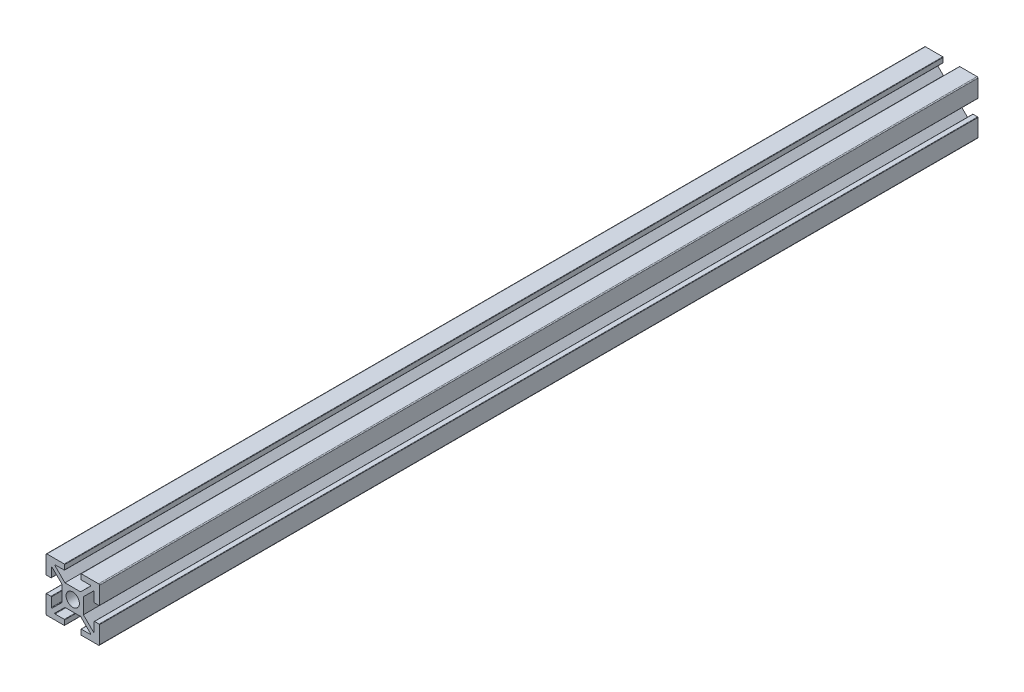
SolidWorks part; units mm, degrees
ref_plane "Front Plane" through (0, 0, 0) normal (0, 0, 1) x (1, 0, 0)
ref_plane "Top Plane" through (0, 0, 0) normal (0, 1, 0) x (1, 0, 0)
ref_plane "Right Plane" through (0, 0, 0) normal (1, 0, 0) x (0, 0, -1)
sketch "Sketch1" plane through (0, 0, 0) normal (0, 0, 1) x (1, 0, 0)
  line L0 (-7.4274, 2.1557) -> (-5.7274, 2.1557)
  line L1 (-0.7274, 9.1557) -> (-7.2274, 9.1557)
  line L2 (-7.5774, 2.3057) -> (-7.5774, 8.8057)
  line L3 (5.4021, 3.1557) -> (-0.4643, 3.1557)
  line L4 (-1.5311, -3.7897) -> (-1.5311, 2.1011)
  line L5 (-5.5774, 2.3057) -> (-5.5774, 5.7419)
  line L6 (-4.1455, 7.1557) -> (-0.7274, 7.1557)
  line L7 (-0.5774, 7.3057) -> (-0.5774, 9.0057)
  line L8 (-5.5774, 7.1557) -> (-1.5311, 3.1557) construction
  line L9 (-5.3219, 5.8486) -> (-1.5311, 2.1011)
  line L10 (-4.2509, 6.899) -> (-0.4643, 3.1557)
  line L11 (10.5152, 7.1557) -> (6.4689, 3.1557) construction
  line L12 (2.4689, -0.8443) -> (2.4689, 10.8443) construction
  line L13 (2.4689, -0.8443) -> (-12.5152, -0.8443) construction
  line L14 (9.1887, 6.899) -> (5.4021, 3.1557)
  line L15 (10.2598, 5.8486) -> (6.4689, 2.1011)
  line L16 (5.5152, 7.3057) -> (5.5152, 9.0057)
  line L17 (9.0833, 7.1557) -> (5.6652, 7.1557)
  line L18 (10.5152, 2.3057) -> (10.5152, 5.7419)
  line L19 (6.4689, -3.7897) -> (6.4689, 2.1011)
  line L20 (12.5152, 2.3057) -> (12.5152, 8.8057)
  line L21 (5.6652, 9.1557) -> (12.1652, 9.1557)
  line L22 (12.3652, 2.1557) -> (10.6652, 2.1557)
  line L23 (10.5152, -8.8443) -> (6.4689, -4.8443) construction
  line L24 (-5.5774, -8.8443) -> (-1.5311, -4.8443) construction
  line L25 (12.3652, -3.8443) -> (10.6652, -3.8443)
  line L26 (5.6652, -10.8443) -> (12.1652, -10.8443)
  line L27 (12.5152, -3.9943) -> (12.5152, -10.4943)
  line L28 (10.5152, -3.9943) -> (10.5152, -7.4305)
  line L29 (9.0833, -8.8443) -> (5.6652, -8.8443)
  line L30 (5.5152, -8.9943) -> (5.5152, -10.6943)
  line L31 (10.2598, -7.5372) -> (6.4689, -3.7897)
  line L32 (9.1887, -8.5876) -> (5.4021, -4.8443)
  line L33 (-4.2509, -8.5876) -> (-0.4643, -4.8443)
  line L34 (-5.3219, -7.5372) -> (-1.5311, -3.7897)
  line L35 (-0.5774, -8.9943) -> (-0.5774, -10.6943)
  line L36 (-4.1455, -8.8443) -> (-0.7274, -8.8443)
  line L37 (-5.5774, -3.9943) -> (-5.5774, -7.4305)
  line L38 (5.4021, -4.8443) -> (-0.4643, -4.8443)
  line L39 (-7.5774, -3.9943) -> (-7.5774, -10.4943)
  line L40 (-0.7274, -10.8443) -> (-7.2274, -10.8443)
  line L41 (-7.4274, -3.8443) -> (-5.7274, -3.8443)
  circle A0 centre (2.4689, -0.8443) radius 2.5
  arc A1 (-7.5774, 8.8057) -> (-7.2274, 9.1557) centre (-7.2274, 8.8057) cw
  arc A2 (-7.4274, 2.1557) -> (-7.5774, 2.3057) centre (-7.4274, 2.3057) cw
  arc A3 (-5.7274, 2.1557) -> (-5.5774, 2.3057) centre (-5.7274, 2.3057) ccw
  arc A4 (-0.7274, 9.1557) -> (-0.5774, 9.0057) centre (-0.7274, 9.0057) cw
  arc A5 (-0.7274, 7.1557) -> (-0.5774, 7.3057) centre (-0.7274, 7.3057) ccw
  arc A6 (-4.2509, 6.899) -> (-4.1455, 7.1557) centre (-4.1455, 7.0057) cw
  arc A7 (-5.3219, 5.8486) -> (-5.5774, 5.7419) centre (-5.4274, 5.7419) ccw
  arc A8 (10.2598, 5.8486) -> (10.5152, 5.7419) centre (10.3652, 5.7419) cw
  arc A9 (9.1887, 6.899) -> (9.0833, 7.1557) centre (9.0833, 7.0057) ccw
  arc A10 (5.6652, 7.1557) -> (5.5152, 7.3057) centre (5.6652, 7.3057) cw
  arc A11 (5.6652, 9.1557) -> (5.5152, 9.0057) centre (5.6652, 9.0057) ccw
  arc A12 (10.6652, 2.1557) -> (10.5152, 2.3057) centre (10.6652, 2.3057) cw
  arc A13 (12.3652, 2.1557) -> (12.5152, 2.3057) centre (12.3652, 2.3057) ccw
  arc A14 (12.5152, 8.8057) -> (12.1652, 9.1557) centre (12.1652, 8.8057) ccw
  arc A15 (12.5152, -10.4943) -> (12.1652, -10.8443) centre (12.1652, -10.4943) cw
  arc A16 (12.3652, -3.8443) -> (12.5152, -3.9943) centre (12.3652, -3.9943) cw
  arc A17 (10.6652, -3.8443) -> (10.5152, -3.9943) centre (10.6652, -3.9943) ccw
  arc A18 (5.6652, -10.8443) -> (5.5152, -10.6943) centre (5.6652, -10.6943) cw
  arc A19 (5.6652, -8.8443) -> (5.5152, -8.9943) centre (5.6652, -8.9943) ccw
  arc A20 (9.1887, -8.5876) -> (9.0833, -8.8443) centre (9.0833, -8.6943) cw
  arc A21 (10.2598, -7.5372) -> (10.5152, -7.4305) centre (10.3652, -7.4305) ccw
  arc A22 (-5.3219, -7.5372) -> (-5.5774, -7.4305) centre (-5.4274, -7.4305) cw
  arc A23 (-4.2509, -8.5876) -> (-4.1455, -8.8443) centre (-4.1455, -8.6943) ccw
  arc A24 (-0.7274, -8.8443) -> (-0.5774, -8.9943) centre (-0.7274, -8.9943) cw
  arc A25 (-0.7274, -10.8443) -> (-0.5774, -10.6943) centre (-0.7274, -10.6943) ccw
  arc A26 (-5.7274, -3.8443) -> (-5.5774, -3.9943) centre (-5.7274, -3.9943) cw
  arc A27 (-7.4274, -3.8443) -> (-7.5774, -3.9943) centre (-7.4274, -3.9943) ccw
  arc A28 (-7.5774, -10.4943) -> (-7.2274, -10.8443) centre (-7.2274, -10.4943) ccw
  point P27 (5.5152, 7.1557)
  point P28 (12.5152, -10.8443)
  point P47 (6.4689, -0.8443)
  point P57 (2.4689, 3.1557)
  point P59 (5.5152, 9.1557)
  point P60 (10.5152, 2.1557)
  point P61 (12.5152, 2.1557)
  point P62 (12.5152, 9.1557)
  point P112 (-1.5311, -0.8443)
  point P113 (12.5152, -3.8443)
  point P114 (10.5152, -3.8443)
  point P115 (5.5152, -10.8443)
  point P116 (2.4689, -4.8443)
  point P117 (-0.5774, -8.8443)
  point P118 (-0.5774, -10.8443)
  point P119 (-5.5774, -3.8443)
  point P120 (5.5152, -8.8443)
  point P121 (-7.5774, -3.8443)
  point P122 (-7.5774, -10.8443)
  dimension "D3" = 0.35
  dimension "D4" = 0.15
  dimension "D5" = 0.15
  dimension "D6" = 0.15
  dimension "D7" = 0.15
  dimension "D8" = 0.15
  dimension "D9" = 0.15
  dimension "D1" = 0.75
  dimension "D2" = 0.75
extrude "Boss-Extrude1" add sketch "Sketch1" along normal blind 330
